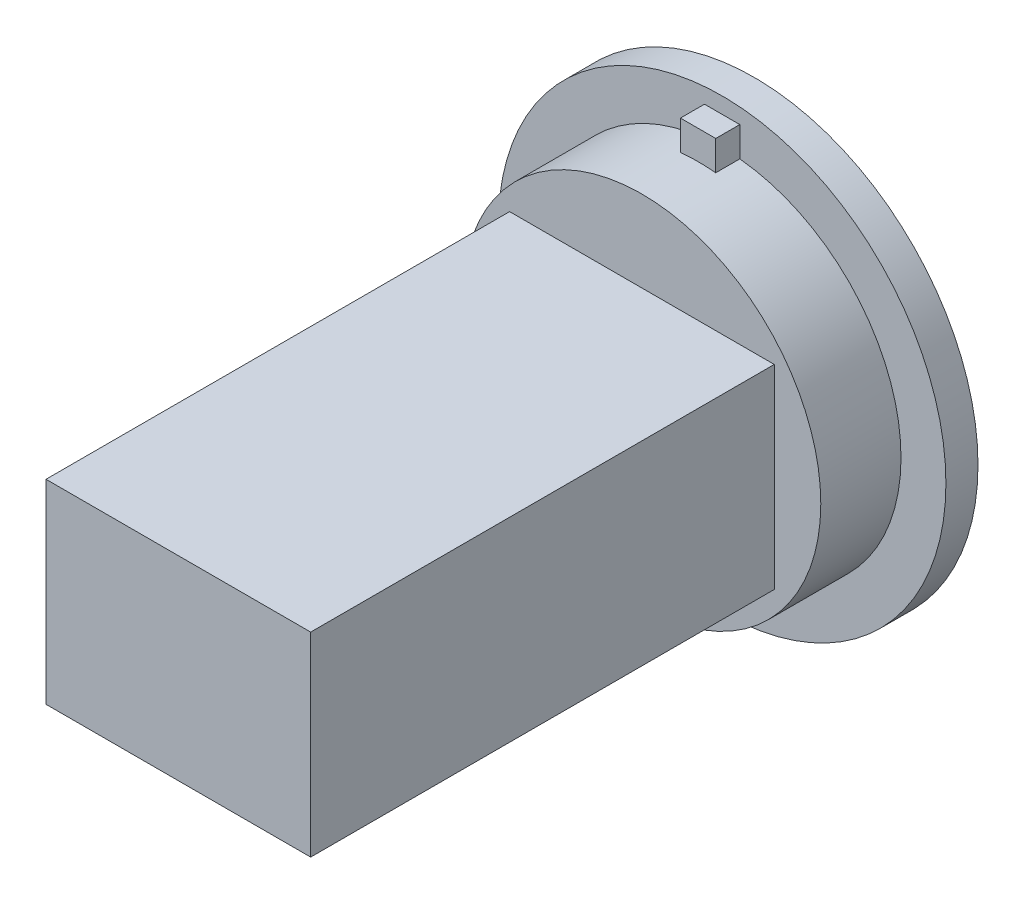
SolidWorks part; units mm, degrees
ref_plane "Plan de face" through (0, 0, 0) normal (0, 0, 1) x (1, 0, 0)
ref_plane "Plan de dessus" through (0, 0, 0) normal (0, 1, 0) x (1, 0, 0)
ref_plane "Plan de droite" through (0, 0, 0) normal (1, 0, 0) x (0, 0, -1)
sketch "Esquisse1" plane through (0, 0, 0) normal (0, 0, 1) x (1, 0, 0)
  circle A0 centre (0, 0) radius 13.95
  dimension "D1" = 27.9
extrude "Boss.-Extru.1" add sketch "Esquisse1" along normal blind 2
sketch "Esquisse2" plane through (0, 0, 2) normal (0, 0, 1) x (1, 0, 0)
  circle A0 centre (0, 0) radius 11.15
  dimension "D1" = 22.3
extrude "Boss.-Extru.2" add sketch "Esquisse2" along normal blind 5
sketch "Esquisse3" plane through (0, 0, 2) normal (0, 0, 1) x (1, 0, 0)
  line L0 (0, 11.15) -> (0, 13.95) construction
  line L1 (1.1, 11.0956) -> (1.1, 12.95)
  line L2 (-1.1, 11.0956) -> (-1.1, 12.95)
  line L3 (-1.1, 12.0228) -> (1.1, 12.0228) construction
  line L4 (-1.1, 12.95) -> (1.1, 12.95)
  circle A0 centre (0, 0) radius 11.15 construction
  circle A1 centre (0, 0) radius 13.95 construction
  circle A2 centre (0, 0) radius 11.15 construction
  arc A3 (-1.1, 11.0956) -> (1.1, 11.0956) centre (0, 0) cw
  point P13 (0, 12.0228)
  circle M5 centre (0, 0) radius 11.15
  dimension "D1" = 2.2
  dimension "D2" = 12.95
extrude "Boss.-Extru.3" add sketch "Esquisse3" along normal blind 1.5 contours L4 L2 L1 M5
sketch "Esquisse4" plane through (0, 0, 7) normal (0, 0, 1) x (1, 0, 0)
  line L1 (-8.25, 6.075) -> (8.25, 6.075)
  line L2 (-8.25, 6.075) -> (-8.25, -6.075)
  line L3 (-8.25, -6.075) -> (8.25, -6.075)
  line L4 (8.25, 6.075) -> (8.25, -6.075)
  circle A2 centre (0, 0) radius 11.15
  circle A3 centre (0, 0) radius 11.15 construction
  point P5 (0, -6.075)
  point P10 (-8.25, 0)
  dimension "D1" = 12.15
  dimension "D2" = 16.5
  dimension "D3" = 0
extrude "Boss.-Extru.4" add sketch "Esquisse4" along normal blind 28.9
sketch "Esquisse6" plane through (0, 0, 0) normal (0, 0, -1) x (-1, 0, 0)
  line L0 (6, 4) -> (1.5, 4)
  line L1 (6, -4) -> (-6, -4)
  line L2 (6, -4) -> (6, 4)
  line L3 (-6, -4) -> (-6, 4)
  line L4 (1.5, 4) -> (1.5, 6)
  line L5 (1.5, 6) -> (-1.5, 6)
  line L6 (-1.5, 6) -> (-1.5, 4)
  line L7 (-1.5, 4) -> (-6, 4)
  point P5 (0, -4)
  point P12 (-6, 0)
  dimension "D1" = 12
  dimension "D2" = 8
  dimension "D3" = 3
  dimension "D4" = 2
extrude "Enlèv. mat.-Extru.1" cut sketch "Esquisse6" against normal blind 10
